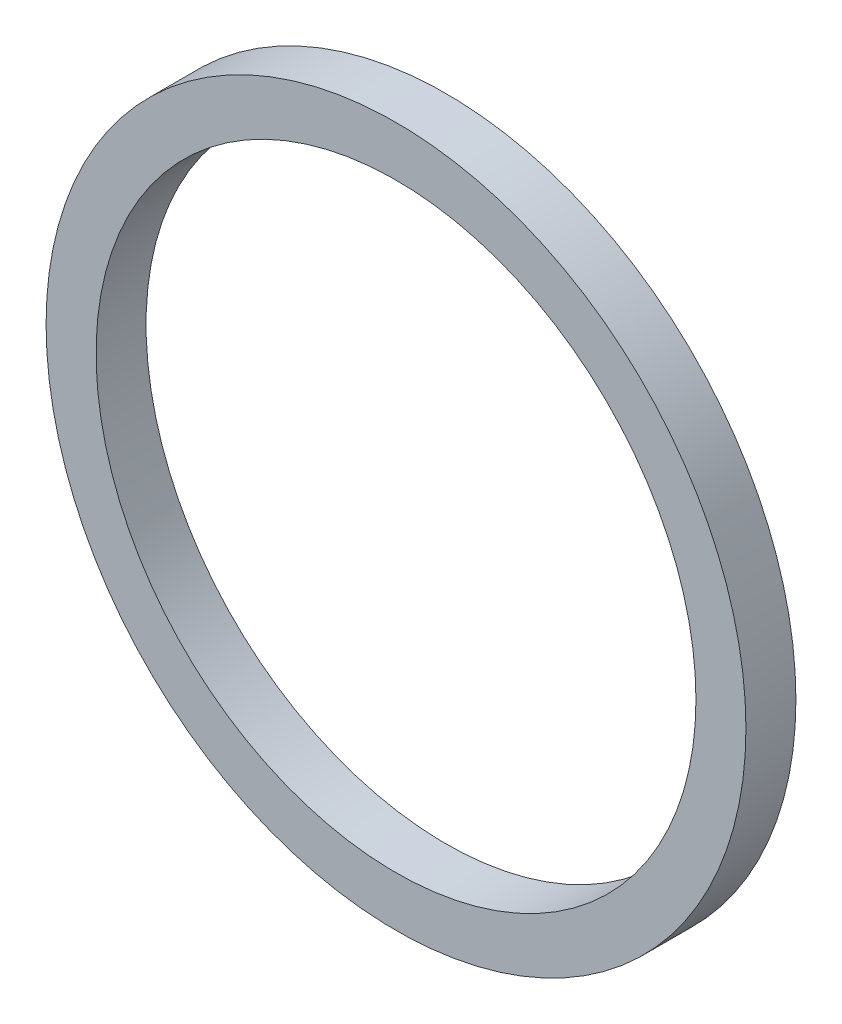
SolidWorks part; units mm, degrees
ref_plane "前视基准面" through (0, 0, 0) normal (0, 0, 1) x (1, 0, 0)
ref_plane "上视基准面" through (0, 0, 0) normal (0, 1, 0) x (1, 0, 0)
ref_plane "右视基准面" through (0, 0, 0) normal (1, 0, 0) x (0, 0, -1)
sketch "草图1" plane through (0, 0, 0) normal (0, 0, 1) x (1, 0, 0)
  circle A0 centre (0, 0) radius 7
  circle A1 centre (0, 0) radius 6
  dimension "D1" = 12
  dimension "D2" = 14
extrude "凸台-拉伸1" add sketch "草图1" along normal blind 1
